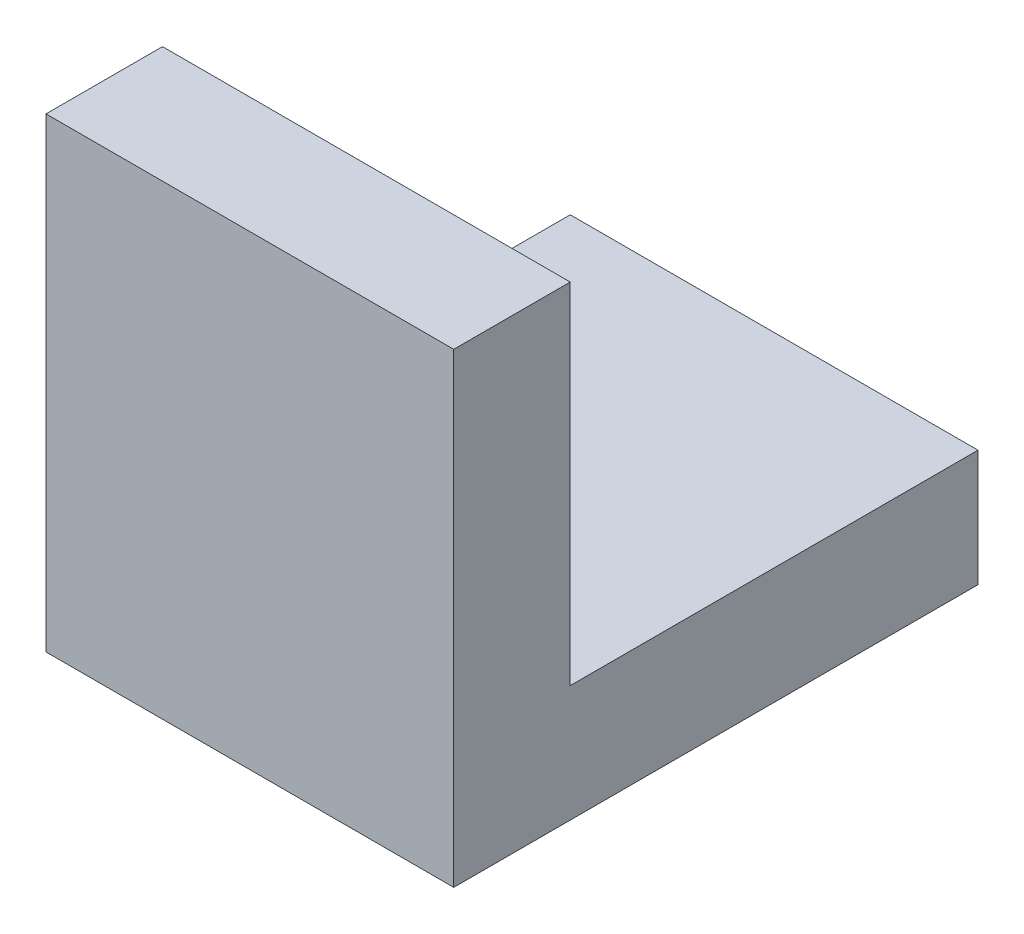
SolidWorks part; units mm, degrees
ref_plane "Ön Düzlem" through (0, 0, 0) normal (0, 0, 1) x (1, 0, 0)
ref_plane "Üst Düzlem" through (0, 0, 0) normal (0, 1, 0) x (1, 0, 0)
ref_plane "Sağ Düzlem" through (0, 0, 0) normal (1, 0, 0) x (0, 0, -1)
sketch "Sketch1" plane through (0, 0, 0) normal (1, 0, 0) x (0, 0, -1)
  line L0 (0, 0) -> (0, 8000)
  line L1 (0, 0) -> (9000, 0)
  line L2 (9000, 0) -> (9000, 2000)
  line L3 (0, 8000) -> (2000, 8000)
  line L4 (9000, 2000) -> (2000, 2000)
  line L5 (2000, 2000) -> (2000, 8000)
extrude "Boss-Extrude2" add sketch "Sketch1" along normal blind 7000
